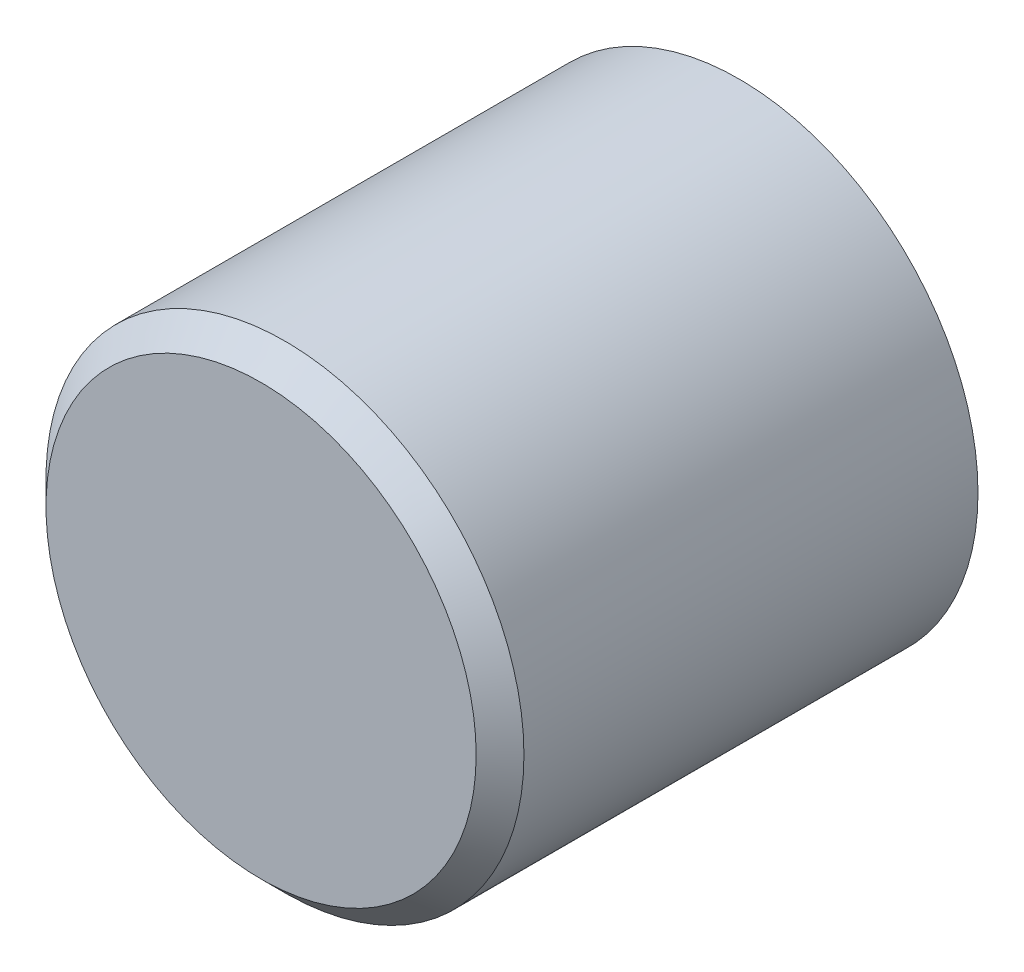
SolidWorks part; units mm, degrees
ref_plane "Front" through (0, 0, 0) normal (0, 0, 1) x (1, 0, 0)
ref_plane "Top" through (0, 0, 0) normal (0, 1, 0) x (1, 0, 0)
ref_plane "Right" through (0, 0, 0) normal (1, 0, 0) x (0, 0, -1)
sketch "COMPONENT_OUTLINE" plane through (0, 0, 0) normal (0, 0, 1) x (1, 0, 0)
  circle A0 centre (0, 0) radius 1
  dimension "D1" = 2
extrude "Extrude1" add sketch "COMPONENT_OUTLINE" along normal blind 2
chamfer "Chamfer1" distance 0.1 angle 45 1 edges at (1, 0, 2)
